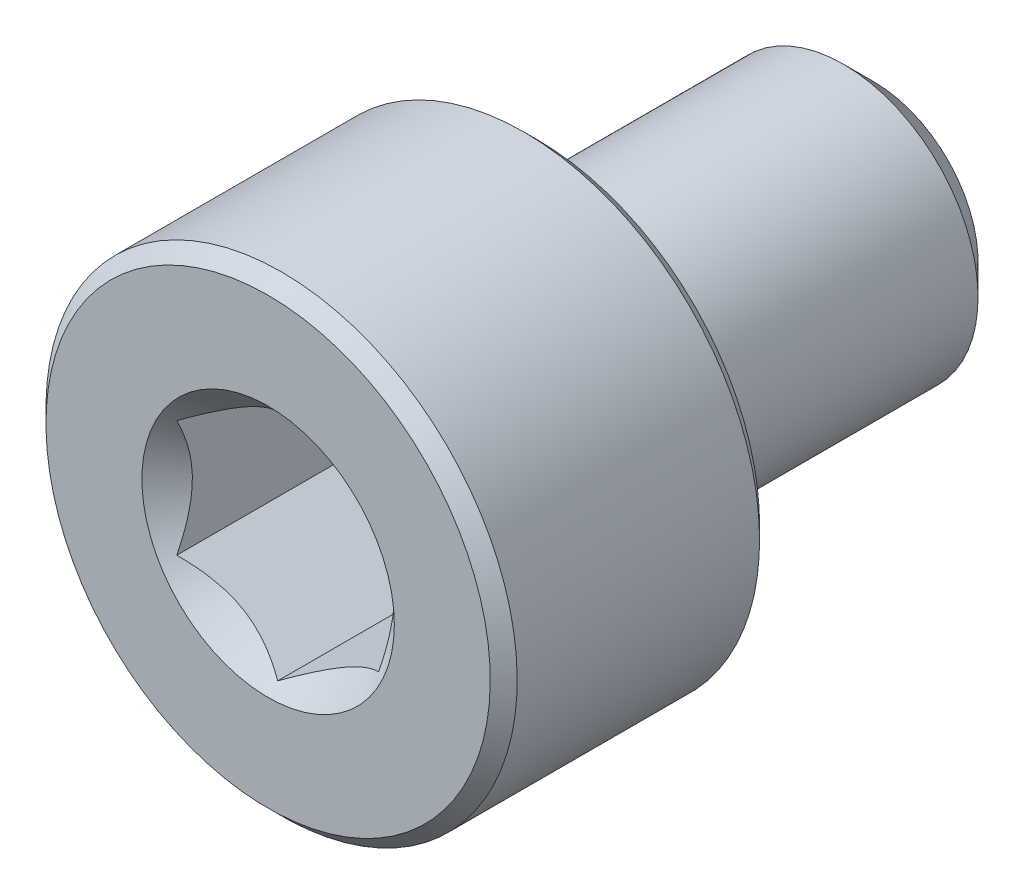
SolidWorks part; units mm, degrees
ref_plane "Front Plane" through (0, 0, 0) normal (0, 0, 1) x (1, 0, 0)
ref_plane "Top Plane" through (0, 0, 0) normal (0, 1, 0) x (1, 0, 0)
ref_plane "Right Plane" through (0, 0, 0) normal (1, 0, 0) x (0, 0, -1)
sketch "Sketch1" plane through (0, 0, 0) normal (1, 0, 0) x (0, 0, -1)
  line L0 (-4.5, 0) -> (4.5, 0) construction
  line L1 (4.5, 0) -> (4.5, 1.5453) construction
  line L2 (4.5, 1.5453) -> (4.0453, 2) construction
  line L3 (4.0453, 2) -> (3.975, 2) construction
  line L4 (3.975, 2) -> (-0.5, 2) construction
  line L5 (-0.5, 2) -> (-0.5, 3.5) construction
  line L6 (-0.5, 3.5) -> (-4.5, 3.5) construction
  line L7 (-4.5, 3.5) -> (-4.5, 0) construction
  line L8 (4.5, 1.5453) -> (4.5, 2) construction
  line L9 (4.4562, 2.0758) -> (4.8062, 1.4696) construction
  line L10 (4.8062, 1.4696) -> (5.1562, 2.0758) construction
  line L11 (5.1562, 2.0758) -> (4.4562, 2.0758) construction
  line L12 (4.8062, 2.0758) -> (4.8062, 2) construction
  line L13 (4.8062, 1.4696) -> (4.8062, 1.5453) construction
  line L14 (4.7625, 1.5453) -> (4.85, 1.5453) construction
  line L15 (4.5, 2) -> (5.1125, 2) construction
  line L16 (4.4781, 2.0379) -> (5.1344, 2.0379) construction
  line L17 (4.5, 0) -> (4.5, -2) construction
  line L18 (-0.7, 3.5) -> (-0.5, 3.3) construction
  line L19 (-4.3, 3.5) -> (-4.5, 3.3) construction
  line L20 (-0.5, 2) -> (-0.5, 0) construction
  line L21 (-0.5, 1) -> (1.1667, 1) construction
  line L22 (1.1667, 1) -> (2.8333, 1) construction
  line L23 (2.8333, 1) -> (4.5, 1) construction
  line L24 (1.1667, 1) -> (1.1667, 2) construction
  line L25 (1.1667, 2) -> (1.1667, 3.5) construction
  line L26 (2.8333, 1) -> (2.8333, 3.5) construction
  point P0 (-4.5, 1.5)
  point P3 (2.75, 2)
  point P4 (0, 0)
  point P18 (2.8333, 2)
  point P22 (4.8062, 1.5453)
  point P24 (3.975, 2)
  point P25 (4.8062, 2)
  point P28 (4.8062, 2.0379)
  point P29 (2.75, -2)
  point P30 (1.1667, 2)
  point P31 (-2.5, 3.5)
  point P37 (-1.2, 3.5)
  point P38 (-4.2, 3.5)
  point P45 (1.1667, 1)
  point P46 (2.8333, 1)
  dimension "D2" = 0.0875
  dimension "D7" = 0.2
  dimension "D8" = 0.2
  dimension "D9" = 0.2
  dimension "D10" = 0.1
  dimension "D11" = 0.5
  dimension "Drive Size" = 3
  dimension "Head Diameter" = 7
  dimension "Head Height" = 4
  dimension "Thread Pitch" = 0.7
  dimension "Thread Size" = 4
  dimension "Length" = 5
  dimension "D12" = 0.525
  dimension "D4" = 1.75
  dimension "D3" = 45
sketch "Sketch2" plane through (0, 0, 0) normal (1, 0, 0) x (0, 0, -1)
  line L0 (-4.5, 0) -> (-4.5, 3.3)
  line L1 (-4.3, 3.5) -> (-0.7, 3.5)
  line L2 (-0.5, 3.3) -> (-0.5, 2.2)
  line L4 (4.0453, 2) -> (4.5, 1.5453)
  line L5 (4.5, 1.5453) -> (4.5, 0)
  line L6 (-0.5, 3.5) -> (-4.5, 3.5) construction
  line L7 (4.5, 0) -> (-4.5, 0)
  line L8 (-4.3, 3.5) -> (-4.5, 3.3) construction
  line L10 (-4.3, 3.5) -> (-4.5, 3.3)
  line L14 (-0.7, 3.5) -> (-0.5, 3.3) construction
  line L16 (-0.7, 3.5) -> (-0.5, 3.3)
  line L17 (-0.5, 2) -> (-0.5, 3.5) construction
  line L19 (-0.3, 2) -> (4.0453, 2)
  line L20 (3.975, 2) -> (-0.5, 2) construction
  arc A1 (-0.5, 2.2) -> (-0.3, 2) centre (-0.3, 2.2) ccw
  dimension "D3" = 0.2
revolve "Revolve1" add sketch "Sketch2" angle 360 about L7
sketch "Sketch3" plane through (0, 0, 4.5) normal (0, 0, 1) x (1, 0, 0)
  line L1 (1.5, -0.866) -> (1.5, 0.866)
  line L2 (1.5, 0.866) -> (0, 1.7321)
  line L3 (0, 1.7321) -> (-1.5, 0.866)
  line L4 (-1.5, 0.866) -> (-1.5, -0.866)
  line L5 (-1.5, -0.866) -> (0, -1.7321)
  line L6 (0, -1.7321) -> (1.5, -0.866)
  circle A0 centre (0, 0) radius 1.5 construction
  circle A1 centre (0, 0) radius 3.5 construction
  circle A2 centre (0, 0) radius 3.5 construction
  circle A3 centre (0, 0) radius 1.7321 construction
  point P13 (0, 0)
extrude "Cut-Extrude1" cut sketch "Sketch3" against normal offset from surface (3 mm away) 1 up to face at (0, 3.3, 0.5)
sketch "Sketch4" plane through (0, 0, 4.5) normal (0, 0, 1) x (1, 0, 0)
  circle A0 centre (0, 0) radius 1.875
  dimension "D1" = 3.75
extrude "Cut-Extrude2" cut sketch "Sketch4" against normal up to vertex (2 mm away) draft 45 up to point (0, 3.5, 2.5)
sketch "Sketch11" plane through (0, 0, 0) normal (1, 0, 0) x (0, 0, -1)
  line L0 (-4.5, 0) -> (4.5, 0) construction
  line L1 (-4.5, 0) -> (4.5, 0) construction
  line L2 (0.4375, 0) -> (0.4375, 2) construction
  line L3 (3.975, 2) -> (-0.5, 2) construction
  line L4 (3.5625, 0) -> (3.5625, 2) construction
  line L6 (4.5, 1.5453) -> (4.5, 2) construction
  point P2 (0.4375, 0)
  point P3 (3.5625, 0)
  dimension "D1" = 0.9375
  dimension "D2" = 0.9375
equation "\"D2@Sketch1\" = \"Thread Pitch@Sketch1\" / 8"
equation "\"D7@Sketch1\" = \"Head Height@Sketch1\" * .05"
equation "\"D8@Sketch1\"=\"D7@Sketch1\""
equation "\"D9@Sketch1\"=\"D7@Sketch1\""
equation "\"D10@Sketch1\"=\"D7@Sketch1\"/2"
equation "\"D11@Sketch1\"=\"D10@Sketch1\"*5"
equation "\"D4@Sketch1\"=\"Thread Pitch@Sketch1\"*2.5"
equation "\"D12@Sketch1\"=\"Thread Pitch@Sketch1\"*.75"
equation "\"D3@Sketch2\" = \"Thread Size@Sketch1\" * 0.05"
equation "\"D1@Sketch11\"=\"Length@Sketch1\"*0.1875"
equation "\"D2@Sketch11\"=\"D1@Sketch11\""
equation "\"D1@Sketch4\"=\"Drive Size@Sketch1\"*1.25"
